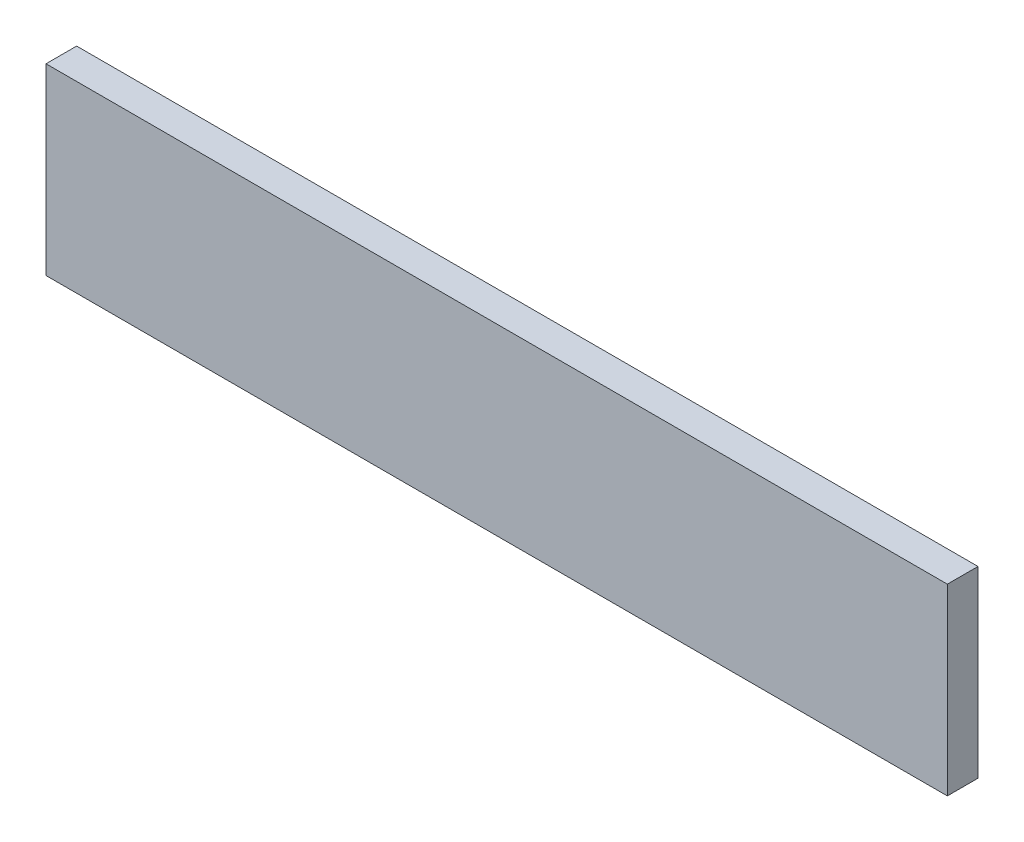
SolidWorks part; units mm, degrees
material "Plain Carbon Steel"
ref_plane "Front Plane" through (0, 0, 0) normal (0, 0, 1) x (1, 0, 0)
ref_plane "Top Plane" through (0, 0, 0) normal (0, 1, 0) x (1, 0, 0)
ref_plane "Right Plane" through (0, 0, 0) normal (1, 0, 0) x (0, 0, -1)
sketch "Sketch1" plane through (0, 0, 0) normal (0, 0, 1) x (1, 0, 0)
  line L0 (-267.6181, -275.3313) -> (-222.9831, -275.3313) construction
  line L1 (-270.3006, -275.3313) -> (29.6994, -275.3313) construction
  line L2 (-270.3006, -275.3313) -> (-270.3006, -341.1571) construction
  line L3 (-270.3006, -341.1571) -> (29.6994, -341.1571) construction
  line L4 (29.6994, -275.3313) -> (29.6994, -341.1571) construction
  line L5 (-270.3006, -308.2442) -> (29.6994, -308.2442) construction
  line L6 (-120.3006, -275.3313) -> (-120.3006, -341.1571) construction
  line L8 (-267.3006, -278.3313) -> (26.6994, -278.3313)
  line L9 (26.6994, -278.3313) -> (26.6994, -338.1571)
  line L10 (-267.3006, -338.1571) -> (26.6994, -338.1571)
  line L11 (-267.3006, -278.3313) -> (-267.3006, -338.1571)
  line L13 (29.6994, -285.3313) -> (29.6994, -331.1571) construction
  line L15 (29.6994, -341.1571) -> (-270.3006, -341.1571) construction
  line L16 (-270.3006, -285.3313) -> (-270.3006, -331.1571) construction
  point P20 (-120.3006, -308.2442)
  dimension "D1" = 3
extrude "Boss-Extrude1" add sketch "Sketch1" along normal blind 10
sketch "Sketch3" plane through (0, 0, 0) normal (0, 0, -1) x (-1, 0, 0)
  line L0 (28.3006, -278.3313) -> (28.3006, -282.3313) construction
  line L1 (-26.6994, -278.3313) -> (267.3006, -278.3313) construction
  line L2 (28.3006, -286.3313) -> (28.3006, -319.1571) construction
  line L3 (28.3006, -323.1571) -> (28.3006, -327.1571) construction
  line L4 (120.3006, -323.1571) -> (120.3006, -286.3313) construction
  line L5 (28.3006, -282.3313) -> (28.3006, -286.3313) construction
  line L6 (28.3006, -319.1571) -> (28.3006, -323.1571) construction
  line L7 (20.3006, -286.3313) -> (24.3006, -286.3313) construction
  line L8 (20.3006, -287.3313) -> (20.3006, -329.1571) construction
  line L9 (28.3006, -286.3313) -> (212.3006, -286.3313) construction
  line L10 (216.3006, -286.3313) -> (220.3006, -286.3313) construction
  line L11 (220.3006, -329.1571) -> (220.3006, -287.3313) construction
  line L12 (24.3006, -286.3313) -> (28.3006, -286.3313) construction
  line L13 (212.3006, -286.3313) -> (216.3006, -286.3313) construction
  line L14 (28.3006, -323.1571) -> (212.3006, -323.1571) construction
  line L15 (212.3006, -323.1571) -> (212.3006, -286.3313) construction
  line L16 (28.3006, -327.1571) -> (28.3006, -331.1571) construction
  line L17 (-29.6994, -331.1571) -> (270.3006, -331.1571) construction
  circle A0 centre (28.3006, -286.3313) radius 4 construction
  point P9 (120.3006, -323.1571)
  dimension "D1" = 8
